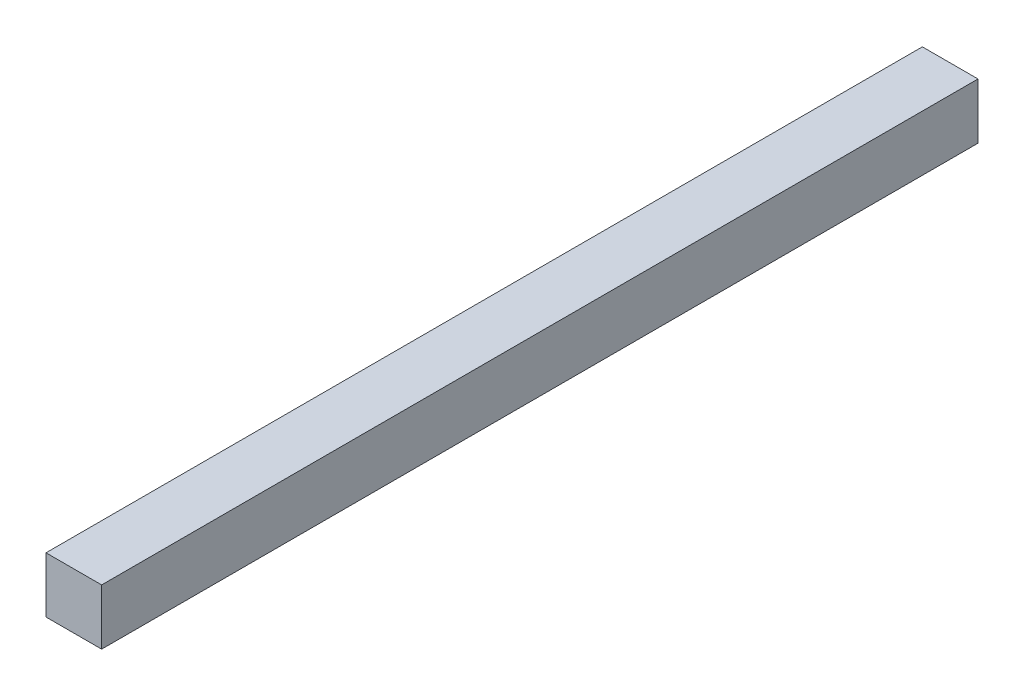
SolidWorks part; units mm, degrees
ref_plane "Front Plane" through (0, 0, 0) normal (0, 0, 1) x (1, 0, 0)
ref_plane "Top Plane" through (0, 0, 0) normal (0, 1, 0) x (1, 0, 0)
ref_plane "Right Plane" through (0, 0, 0) normal (1, 0, 0) x (0, 0, -1)
sketch "Sketch1" plane through (0, 0, 0) normal (0, 0, 1) x (1, 0, 0)
  line L1 (1.5875, 1.5875) -> (-1.5875, 1.5875)
  line L2 (1.5875, 1.5875) -> (1.5875, -1.5875)
  line L3 (1.5875, -1.5875) -> (-1.5875, -1.5875)
  line L4 (-1.5875, 1.5875) -> (-1.5875, -1.5875)
  line L5 (1.5875, 1.5875) -> (-1.5875, -1.5875) construction
  line L6 (1.5875, -1.5875) -> (-1.5875, 1.5875) construction
  point P0 (0, 0)
  dimension "D1" = 3.175
extrude "Boss-Extrude1" add sketch "Sketch1" along normal blind 50
